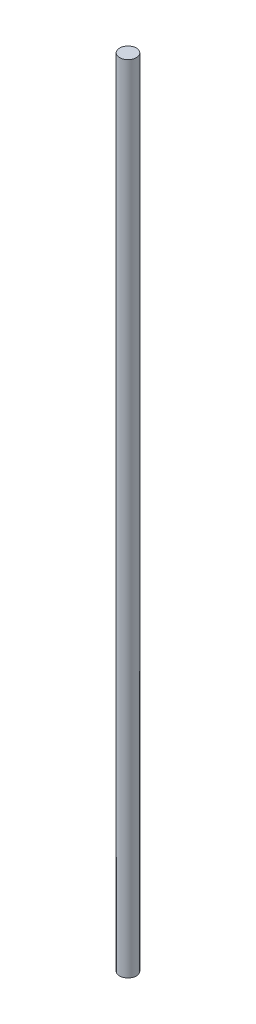
SolidWorks part; units mm, degrees
material "AISI 304"
ref_plane "前视基准面" through (0, 0, 0) normal (0, 0, 1) x (1, 0, 0)
ref_plane "上视基准面" through (0, 0, 0) normal (0, 1, 0) x (1, 0, 0)
ref_plane "右视基准面" through (0, 0, 0) normal (1, 0, 0) x (0, 0, -1)
sketch "草图1" plane through (0, 0, 0) normal (0, 1, 0) x (1, 0, 0)
  circle A0 centre (0, 0) radius 1.05
  dimension "D1" = 2.1
extrude "凸台-拉伸1" add sketch "草图1" along normal blind 100
